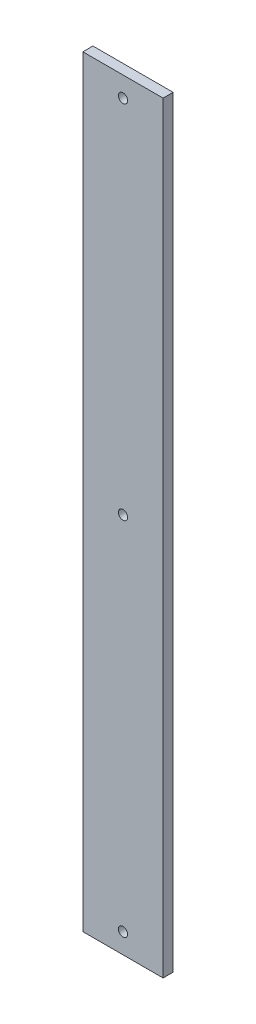
SolidWorks part; units mm, degrees
ref_plane "Front Plane" through (0, 0, 0) normal (0, 0, 1) x (1, 0, 0)
ref_plane "Top Plane" through (0, 0, 0) normal (0, 1, 0) x (1, 0, 0)
ref_plane "Right Plane" through (0, 0, 0) normal (1, 0, 0) x (0, 0, -1)
sketch "Sketch2" plane through (0, 0, 0) normal (0, 0, 1) x (1, 0, 0)
  line L0 (12.7, 241.3) -> (12.7, 0) construction
  line L1 (0, 0) -> (25.4, 0)
  line L2 (0, 0) -> (0, 241.3)
  line L3 (0, 241.3) -> (25.4, 241.3)
  line L4 (25.4, 0) -> (25.4, 241.3)
  line L5 (0, 120.65) -> (25.4, 120.65) construction
  circle A0 centre (12.7, 234.95) radius 1.4605
  circle A1 centre (12.7, 6.35) radius 1.4605
  circle A2 centre (12.7, 120.65) radius 1.4605
  dimension "D3" = 2.921
  dimension "D5" = 2.921
  dimension "D7" = 2.921
  dimension "D1" = 241.3
  dimension "D2" = 25.4
  dimension "D4" = 6.35
  dimension "D6" = 6.35
extrude "Boss-Extrude1" add sketch "Sketch2" along normal blind 3.175
